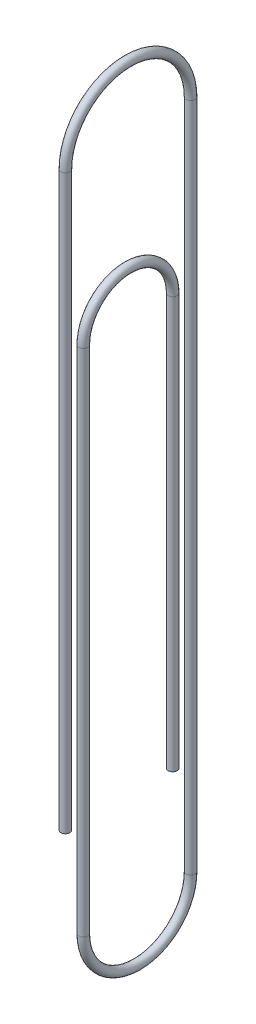
SolidWorks part; units mm, degrees
material "AISI 304"
ref_plane "Front Plane" through (0, 0, 0) normal (1, 0, 0) x (0, 1, 0)
ref_plane "Top Plane" through (0, 0, 0) normal (0, 0, 1) x (0, 1, 0)
ref_plane "Right Plane" through (0, 0, 0) normal (0, 1, 0) x (-1, 0, 0)
sketch "Sketch1" plane through (0, 0, 0) normal (1, 0, 0) x (0, 1, 0)
  line L0 (0, 0) -> (32, 0)
  line L1 (32, -7) -> (-5.5, -7)
  line L2 (-5.5, -1) -> (23, -1)
  line L3 (23, -6) -> (0, -6)
  line L4 (0, 5.2583) -> (0, -6.5245) construction
  arc A0 (32, 0) -> (32, -7) centre (32, -3.5) cw
  arc A1 (-5.5, -7) -> (-5.5, -1) centre (-5.5, -4) cw
  arc A2 (23, -1) -> (23, -6) centre (23, -3.5) cw
  point P14 (0, -6)
  point P15 (0, -6.5245)
  point P16 (-0.3519, -6)
  dimension "D4" = 3.5
  dimension "D5" = 2.5
  dimension "D6" = 3
  dimension "D1" = 28.5
  dimension "D2" = 32
  dimension "D3" = 9
sketch "Sketch2" plane through (0, 0, 0) normal (0, 1, 0) x (-1, 0, 0)
  circle A0 centre (0, 0) radius 0.25
  dimension "D1" = 0.5
sweep "Sweep1" add profiles "Sketch2" path "Sketch1"
equation "\"A\"= 19 * 1.5"
equation "\"D1@Sketch1\"=\"A\""
equation "\"B\" = 16 * 2"
equation "\"D2@Sketch1\"=\"B\""
equation "\"C\"= 9"
equation "\"D3@Sketch1\"=\"C\""
